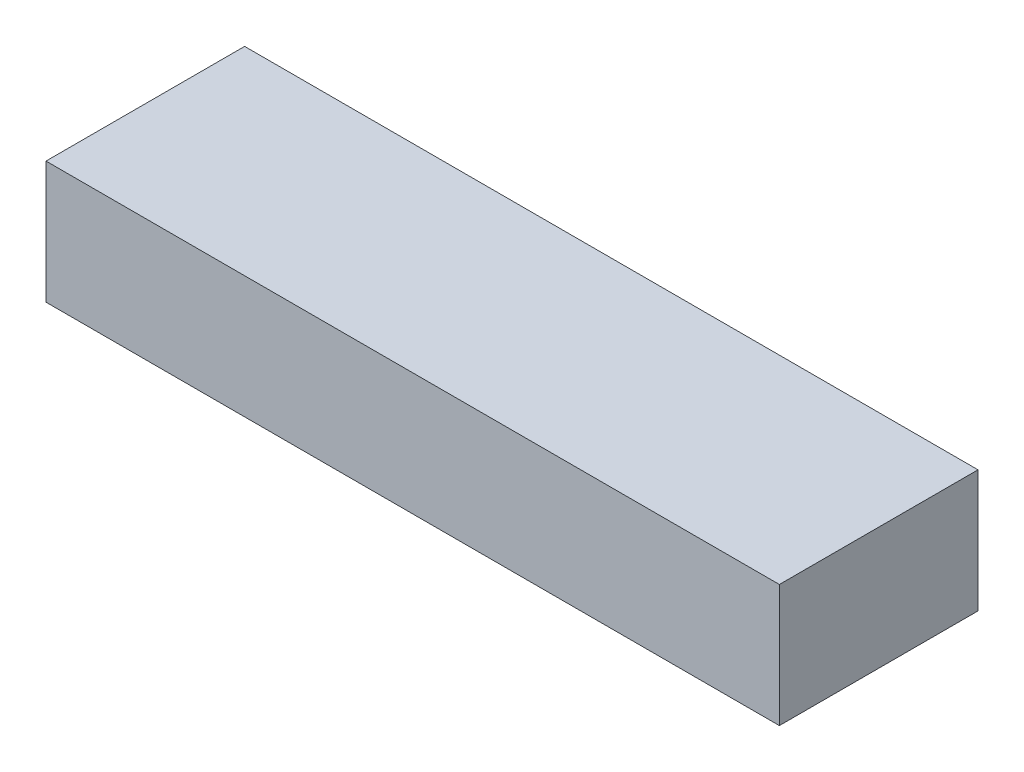
SolidWorks part; units mm, degrees
ref_plane "Front Plane" through (0, 0, 0) normal (0, 0, 1) x (1, 0, 0)
ref_plane "Top Plane" through (0, 0, 0) normal (0, 1, 0) x (1, 0, 0)
ref_plane "Right Plane" through (0, 0, 0) normal (1, 0, 0) x (0, 0, -1)
sketch "Sketch1" plane through (0, 0, 0) normal (0, 1, 0) x (1, 0, 0)
  line L1 (0, 0) -> (152.4, 0)
  line L2 (0, 0) -> (0, 41.275)
  line L3 (0, 41.275) -> (152.4, 41.275)
  line L4 (152.4, 0) -> (152.4, 41.275)
  dimension "D1" = 152.4
  dimension "D2" = 41.275
extrude "Boss-Extrude1" add sketch "Sketch1" along normal blind 25.4
